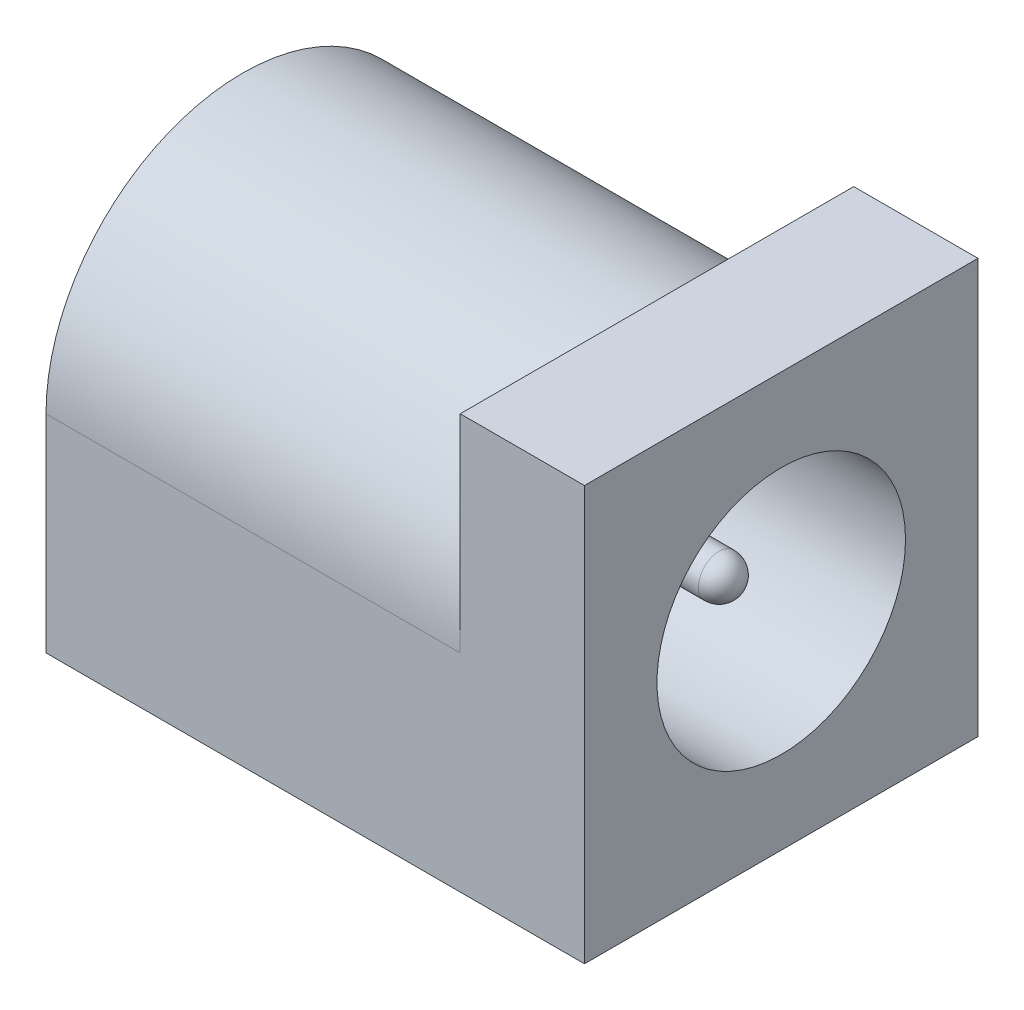
SolidWorks part; units mm, degrees
ref_plane "Front Plane" through (0, 0, 0) normal (0, 0, 1) x (1, 0, 0)
ref_plane "Top Plane" through (0, 0, 0) normal (0, 1, 0) x (1, 0, 0)
ref_plane "Right Plane" through (0, 0, 0) normal (1, 0, 0) x (0, 0, -1)
sketch "Sketch1" plane through (0, 0, 0) normal (1, 0, 0) x (0, 0, -1)
  line L1 (-4.75, -2.5) -> (4.75, -2.5)
  line L2 (-4.75, -2.5) -> (-4.75, 2.5)
  line L4 (4.75, -2.5) -> (4.75, 2.5)
  line L5 (-4.75, -2.5) -> (4.75, 2.5) construction
  line L6 (-4.75, 2.5) -> (4.75, -2.5) construction
  arc A0 (-4.75, 2.5) -> (4.75, 2.5) centre (0, 2.5) cw
  point P0 (0, 0)
  dimension "D3" = 4.75
  dimension "D1" = 9.5
  dimension "D2" = 5
extrude "Boss-Extrude1" add sketch "Sketch1" along normal blind 10
sketch "Sketch2" plane through (10, 0, 0) normal (1, 0, 0) x (0, 0, -1)
  line L5 (-4.75, -2.5) -> (4.75, -2.5) construction
  line L6 (-4.75, 7.5) -> (4.75, 7.5)
  line L8 (-4.75, 7.5) -> (-4.75, -2.5)
  line L9 (-4.75, -2.5) -> (4.75, -2.5)
  line L10 (4.75, 7.5) -> (4.75, -2.5)
  point P4 (5.1872, -2.9097)
  dimension "D1" = 9.5
  dimension "D2" = 4.75
  dimension "D3" = 10
extrude "Boss-Extrude2" add sketch "Sketch2" along normal blind 3
sketch "Sketch3" plane through (13, 0, 0) normal (1, 0, 0) x (0, 0, -1)
  circle A0 centre (0, 2.5) radius 3
  arc A1 (4.75, 2.5) -> (-4.75, 2.5) centre (0, 2.5) ccw construction
  dimension "D1" = 6
extrude "Cut-Extrude1" cut sketch "Sketch3" against normal blind 12
sketch "Sketch4" plane through (1, 0, 0) normal (1, 0, 0) x (0, 0, -1)
  circle A0 centre (0, 2.5) radius 0.5
  dimension "D1" = 1
extrude "Boss-Extrude3" add sketch "Sketch4" along normal blind 11
fillet "Fillet1" radius 0.5 1 edges at (12, 2.5, -0.5)
